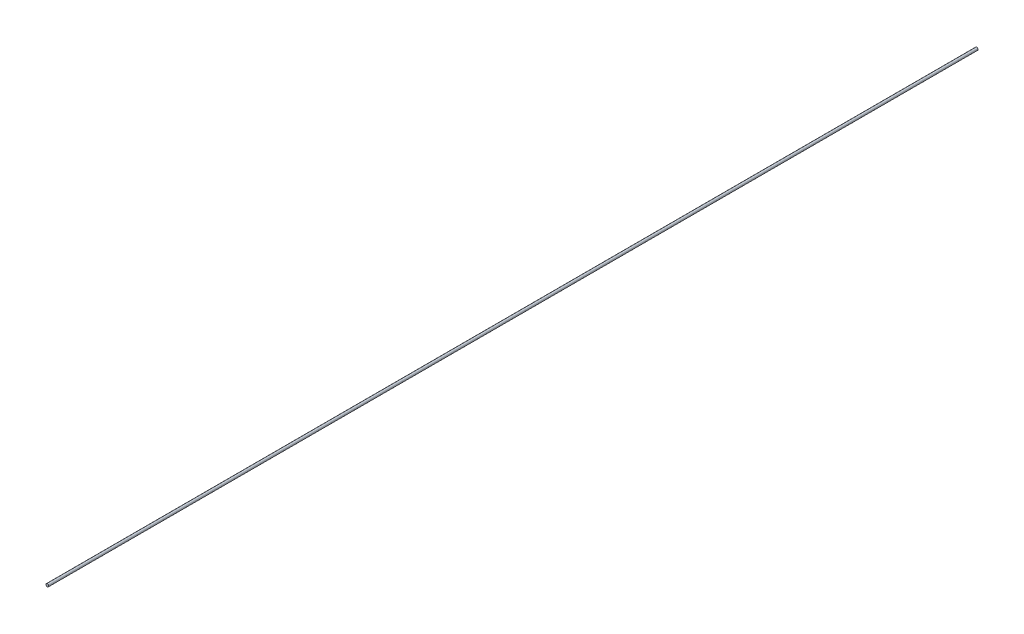
SolidWorks part; units mm, degrees
ref_plane "Front Plane" through (0, 0, 0) normal (0, 0, 1) x (1, 0, 0)
ref_plane "Top Plane" through (0, 0, 0) normal (0, 1, 0) x (1, 0, 0)
ref_plane "Right Plane" through (0, 0, 0) normal (1, 0, 0) x (0, 0, -1)
sketch "CurveSketch" plane through (0, 0, 0) normal (0, 0, 1) x (1, 0, 0)
  circle A0 centre (-3.719, 5.173) radius 0.017
  dimension "D1" = 0.017
extrude "CurveBoss" add sketch "CurveSketch" along normal blind 11.731
